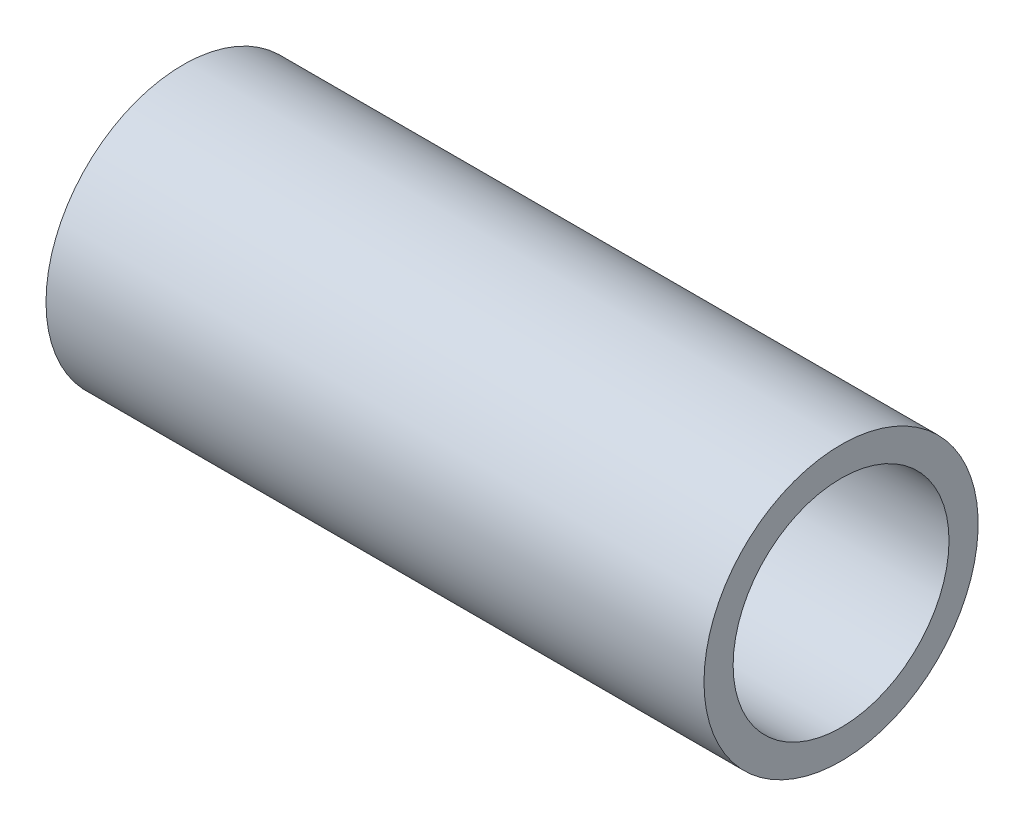
SolidWorks part; units mm, degrees
ref_plane "Front" through (0, 0, 0) normal (0, 0, 1) x (1, 0, 0)
ref_plane "Top" through (0, 0, 0) normal (0, 1, 0) x (1, 0, 0)
ref_plane "Right" through (0, 0, 0) normal (1, 0, 0) x (0, 0, -1)
sketch "Sketch1" plane through (0, 0, 0) normal (1, 0, 0) x (0, 0, -1)
  circle A0 centre (0, 0) radius 12.5
  circle A1 centre (0, 0) radius 15.875
  dimension "D1" = 25
  dimension "D2" = 31.75
extrude "Base-Extrude" add sketch "Sketch1" along normal blind 76.2
